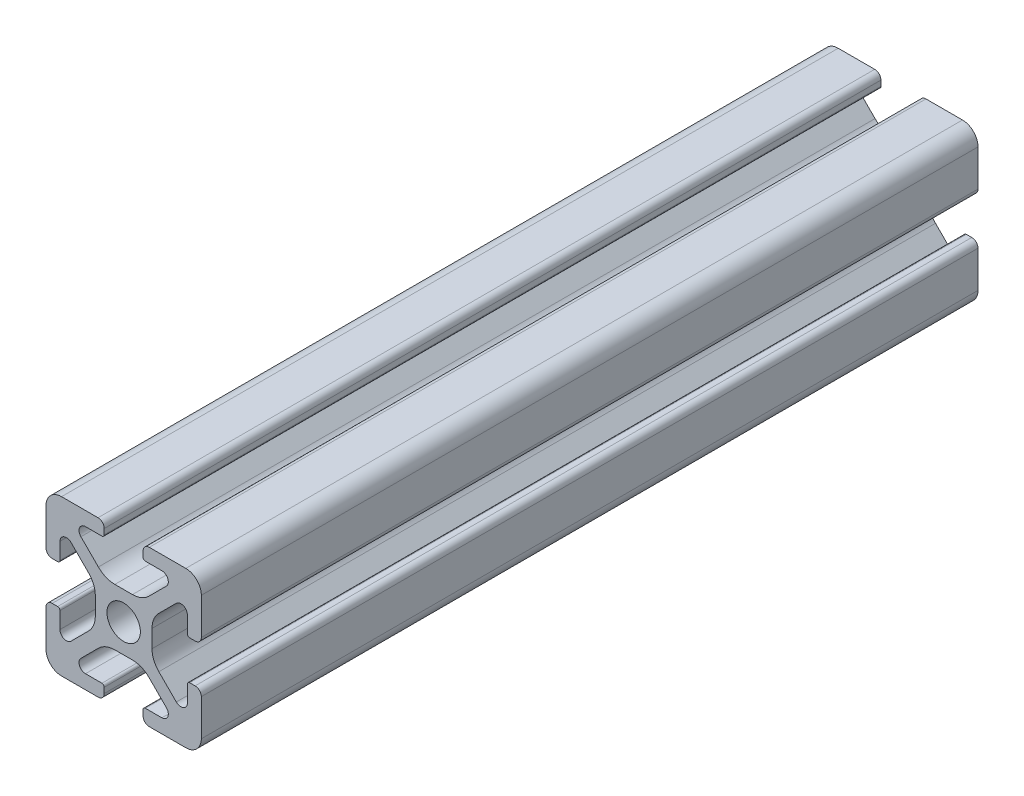
SolidWorks part; units mm, degrees
material "Alliage 1060"
ref_plane "Plan de face" through (0, 0, 0) normal (0, 0, 1) x (1, 0, 0)
ref_plane "Plan de dessus" through (0, 0, 0) normal (0, 1, 0) x (1, 0, 0)
ref_plane "Plan de droite" through (0, 0, 0) normal (1, 0, 0) x (0, 0, -1)
ref_plane "Plan1" through (0, 0, 0) normal (0, 0, -1) x (-1, 0, 0)
sketch "Esquisse1" plane through (0, 0, 0) normal (0, 0, -1) x (-1, 0, 0)
  line L0 (-18, 0) -> (-13.3, 0)
  line L1 (-12.8, 1.8) -> (-14.9184, 1.8)
  line L2 (-15.5064, 3.2196) -> (-13.2547, 5.4713)
  line L3 (-11.1334, 6.35) -> (-8.8666, 6.35)
  line L4 (-6.7453, 5.4713) -> (-4.4936, 3.2196)
  line L5 (-5.0816, 1.8) -> (-7.2, 1.8)
  line L6 (-6.7, 0) -> (-2, 0)
  line L7 (0, 2) -> (0, 6.7)
  line L8 (-1.8, 7.2) -> (-1.8, 5.0816)
  line L9 (-3.2196, 4.4936) -> (-5.4713, 6.7453)
  line L10 (-6.35, 8.8666) -> (-6.35, 11.1334)
  line L11 (-5.4713, 13.2547) -> (-3.2196, 15.5064)
  line L12 (-1.8, 14.9184) -> (-1.8, 12.8)
  line L13 (0, 13.3) -> (0, 18)
  line L14 (-2, 20) -> (-6.7, 20)
  line L15 (-7.2, 18.2) -> (-5.0816, 18.2)
  line L16 (-4.4936, 16.7804) -> (-6.7453, 14.5287)
  line L17 (-8.8666, 13.65) -> (-11.1334, 13.65)
  line L18 (-13.2547, 14.5287) -> (-15.5064, 16.7804)
  line L19 (-14.9184, 18.2) -> (-12.8, 18.2)
  line L20 (-13.3, 20) -> (-18, 20)
  line L21 (-20, 18) -> (-20, 13.3)
  line L22 (-16.7804, 15.5064) -> (-14.5287, 13.2547)
  line L23 (-13.65, 11.1334) -> (-13.65, 8.8666)
  line L24 (-14.5287, 6.7453) -> (-16.7804, 4.4936)
  line L25 (-18.2, 5.0816) -> (-18.2, 7.2)
  line L26 (-20, 6.7) -> (-20, 2)
  arc A0 (-20, 2) -> (-18, 0) centre (-18, 2) ccw
  arc A1 (-13.3, 0) -> (-12.5, 0.8) centre (-13.3, 0.8) ccw
  arc A2 (-12.5, 1.5) -> (-12.8, 1.8) centre (-12.8, 1.5) ccw
  arc A3 (-14.9184, 1.8) -> (-15.5064, 3.2196) centre (-14.9184, 2.6316) cw
  arc A4 (-13.2547, 5.4713) -> (-11.1334, 6.35) centre (-11.1334, 3.35) cw
  arc A5 (-8.8666, 6.35) -> (-6.7453, 5.4713) centre (-8.8666, 3.35) cw
  arc A6 (-4.4936, 3.2196) -> (-5.0816, 1.8) centre (-5.0816, 2.6316) cw
  arc A7 (-7.2, 1.8) -> (-7.5, 1.5) centre (-7.2, 1.5) ccw
  arc A8 (-7.5, 0.8) -> (-6.7, 0) centre (-6.7, 0.8) ccw
  arc A9 (-2, 0) -> (0, 2) centre (-2, 2) ccw
  arc A10 (0, 6.7) -> (-0.8, 7.5) centre (-0.8, 6.7) ccw
  arc A11 (-1.5, 7.5) -> (-1.8, 7.2) centre (-1.5, 7.2) ccw
  arc A12 (-1.8, 5.0816) -> (-3.2196, 4.4936) centre (-2.6316, 5.0816) cw
  arc A13 (-5.4713, 6.7453) -> (-6.35, 8.8666) centre (-3.35, 8.8666) cw
  arc A14 (-6.35, 11.1334) -> (-5.4713, 13.2547) centre (-3.35, 11.1334) cw
  arc A15 (-3.2196, 15.5064) -> (-1.8, 14.9184) centre (-2.6316, 14.9184) cw
  arc A16 (-1.8, 12.8) -> (-1.5, 12.5) centre (-1.5, 12.8) ccw
  arc A17 (-0.8, 12.5) -> (0, 13.3) centre (-0.8, 13.3) ccw
  arc A18 (0, 18) -> (-2, 20) centre (-2, 18) ccw
  arc A19 (-6.7, 20) -> (-7.5, 19.2) centre (-6.7, 19.2) ccw
  arc A20 (-7.5, 18.5) -> (-7.2, 18.2) centre (-7.2, 18.5) ccw
  arc A21 (-5.0816, 18.2) -> (-4.4936, 16.7804) centre (-5.0816, 17.3684) cw
  arc A22 (-6.7453, 14.5287) -> (-8.8666, 13.65) centre (-8.8666, 16.65) cw
  arc A23 (-11.1334, 13.65) -> (-13.2547, 14.5287) centre (-11.1334, 16.65) cw
  arc A24 (-15.5064, 16.7804) -> (-14.9184, 18.2) centre (-14.9184, 17.3684) cw
  arc A25 (-12.8, 18.2) -> (-12.5, 18.5) centre (-12.8, 18.5) ccw
  arc A26 (-12.5, 19.2) -> (-13.3, 20) centre (-13.3, 19.2) ccw
  arc A27 (-18, 20) -> (-20, 18) centre (-18, 18) ccw
  arc A28 (-20, 13.3) -> (-19.2, 12.5) centre (-19.2, 13.3) ccw
  arc A29 (-18.5, 12.5) -> (-18.2, 12.8) centre (-18.5, 12.8) ccw
  arc A30 (-18.2, 14.9184) -> (-16.7804, 15.5064) centre (-17.3684, 14.9184) cw
  arc A31 (-14.5287, 13.2547) -> (-13.65, 11.1334) centre (-16.65, 11.1334) cw
  arc A32 (-13.65, 8.8666) -> (-14.5287, 6.7453) centre (-16.65, 8.8666) cw
  arc A33 (-16.7804, 4.4936) -> (-18.2, 5.0816) centre (-17.3684, 5.0816) cw
  arc A34 (-18.2, 7.2) -> (-18.5, 7.5) centre (-18.5, 7.2) ccw
  arc A35 (-19.2, 7.5) -> (-20, 6.7) centre (-19.2, 6.7) ccw
  circle A36 centre (-10, 10) radius 2.15
  spline S0 degree 1 poles (-12.5, 1.5) (-12.5, 0.8) knots 0 0 0.7 0.7
  spline S1 degree 1 poles (-7.5, 0.8) (-7.5, 1.5) knots 0 0 0.7 0.7
  spline S2 degree 1 poles (-1.5, 7.5) (-0.8, 7.5) knots 0 0 0.7 0.7
  spline S3 degree 1 poles (-0.8, 12.5) (-1.5, 12.5) knots 0 0 0.7 0.7
  spline S4 degree 1 poles (-7.5, 18.5) (-7.5, 19.2) knots 0 0 0.7 0.7
  spline S5 degree 1 poles (-12.5, 19.2) (-12.5, 18.5) knots 0 0 0.7 0.7
  spline S6 degree 1 poles (-18.5, 12.5) (-19.2, 12.5) knots 0 0 0.7 0.7
  spline S7 degree 1 poles (-18.2, 14.9184) (-18.2, 12.8) knots 0 0 2.118424 2.118424
  spline S8 degree 1 poles (-19.2, 7.5) (-18.5, 7.5) knots 0 0 0.7 0.7
extrude "Extrusion1" add sketch "Esquisse1" against normal blind 100
